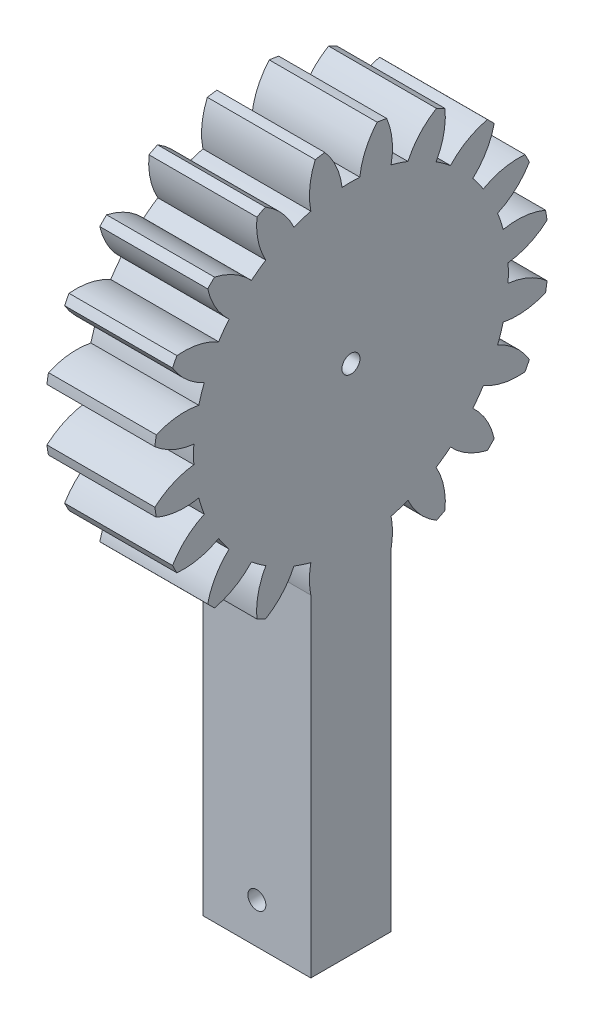
SolidWorks part; units mm, degrees
ref_plane "Plane1" through (0, 0, 0) normal (0, 0, 1) x (1, 0, 0)
ref_plane "Plane2" through (0, 0, 0) normal (0, 1, 0) x (1, 0, 0)
ref_plane "Plane3" through (0, 0, 0) normal (1, 0, 0) x (0, 0, -1)
other "Configuration Table"
sketch "HoldingSke" plane through (0, 0, 0) normal (0, 1, 0) x (1, 0, 0)
  line L0 (0, 0) -> (0.1879, -0.0684)
  line L1 (-15, 0) -> (100, 0) construction
  line L2 (0, 0) -> (-2.1039, 2.3779)
  line L3 (0, 0) -> (-11.863, 4.5341)
  line L4 (0, 0) -> (8.1152, 2.9537)
  line L5 (0, 0) -> (-46.8476, -17.4728)
  line L6 (0, 0) -> (-24.8689, -16.7791)
  line L7 (-2.1039, 2.3779) -> (8.6586, 51.2059)
  line L8 (-76.2, 54.61) -> (-75.3, 54.61)
  line L9 (-71.009, 38.7566) -> (-53.1078, 45.2721)
  line L10 (-76.2, 71.12) -> (104.1128, 71.12)
  line L11 (0, 0) -> (-30, 0)
  line L12 (-76.2, 101.6) -> (-76.033, 101.6)
  line L13 (24.9733, 27.94) -> (52.9518, 28.4284)
  line L14 (24.9733, 27.94) -> (24.9743, 27.94)
  line L15 (24.9733, 27.94) -> (100.4006, 29.5858)
  line L16 (-63.627, -5) -> (-12.827, -5)
  circle A0 centre (0, 0) radius 2.5
  circle A1 centre (0, 0) radius 37.5
  circle A2 centre (0, 0) radius 37.5
  circle A3 centre (0, 0) radius 2.5
  dimension "MHD" = 75
  dimension "Hub_dia" = 75
  dimension "Bore" = 5
  dimension "MBD" = 5
  dimension "Num_teeth" = 20
  dimension "Pitch" = 0.2
  dimension "Overall_len" = 50
  dimension "Show_teeth" = 20
  dimension "Thickness" = 30
  dimension "OAL" = 50.0001
  dimension "T_dim" = 0.9
  dimension "Ap" = 20
  dimension "H" = 19.05
  dimension "Pitch_radius" = 180.3128
  dimension "Width" = 30
  dimension "Backlash" = 0.167
  dimension "Addendum_fac" = 1
  dimension "Dedendum_fac" = 1.25
  dimension "Clearance_fac" = 0.25
  dimension "Dedendum_add" = 0.001
  dimension "Module" = 5
sketch "BasProSke" plane through (0, 0, 0) normal (0, 1, 0) x (1, 0, 0)
  line L0 (-10, 0) -> (60, 0) construction
  line L1 (0, 0) -> (0, 55)
  line L2 (0, 0) -> (30, 0)
  line L3 (30, 0) -> (30, 55)
  line L4 (30, 55) -> (0, 55)
  dimension "Thickness" = 30
  dimension "Diameter" = 110
revolve "Base-Revolve" add sketch "BasProSke" angle 360 about L0
sketch "TooCutSke" plane through (0, 0, 0) normal (1, 0, 0) x (0, 0, -1)
  line L1 (0, 0) -> (0, 107) construction
  line L2 (0, 0) -> (-4.2151, 49.822) construction
  line L3 (0, 0) -> (-15.6021, 98.5081) construction
  line L4 (-4.2151, 49.822) -> (-7.8011, 49.254) construction
  arc A0 (2.4648, 43.6795) -> (-2.4648, 43.6795) centre (0, 0) ccw
  arc A1 (7.3009, 54.5389) -> (-7.3009, 54.5389) centre (0, 0) ccw
  circle A2 centre (0, 0) radius 50 construction
  circle A3 centre (0, 0) radius 46.9846 construction
  arc A4 (-2.4648, 43.6795) -> (-7.3009, 54.5389) centre (-22.3276, 41.3405) ccw
  arc A5 (7.3009, 54.5389) -> (2.4648, 43.6795) centre (22.3276, 41.3405) ccw
  dimension "Root_dia" = 87.498
  dimension "Overcut_dia" = 110.0508
  dimension "Pitch_dia" = 100
  dimension "Base_dia" = 93.9693
  dimension "Flank_rad" = 20
  dimension "Half_ang" = 9
  dimension "Half_CT" = 3.6307
extrude "ToothCut" cut sketch "TooCutSke" along normal through all
fillet "Breaks" [suppressed] radius 0.1
fillet "RootFillets" [suppressed] radius 1.251
pattern_circular "TeethCuts" count 20 over 360 about axis through (0, 0, 0) along (1, 0, 0) of "ToothCut", "RootFillets", "Breaks"
sketch "HubNeaOneSke" plane through (0, 0, 0) normal (-1, 0, 0) x (0, 0, 1)
  circle A0 centre (0, 0) radius 37.5
  dimension "Diameter" = 75
extrude "HubNearOne" [suppressed] add sketch "HubNeaOneSke" along normal blind 20.0001
sketch "HubNeaBotSke" plane through (0, 0, 0) normal (-1, 0, 0) x (0, 0, 1)
  circle A0 centre (0, 0) radius 37.5
  dimension "Diameter" = 75
extrude "HubNearBoth" [suppressed] add sketch "HubNeaBotSke" along normal blind 10
ref_plane "FarPln" through (30, 0, 0) normal (1, 0, 0) x (0, 0, -1)
sketch "HubFarSke" plane through (30, 0, 0) normal (1, 0, 0) x (0, 0, -1)
  circle A0 centre (0, 0) radius 37.5
  dimension "Diameter" = 75
extrude "HubFar" [suppressed] add sketch "HubFarSke" along normal blind 10
sketch "BorSke" plane through (0, 0, 0) normal (1, 0, 0) x (0, 0, -1)
  circle A0 centre (0, 0) radius 2.5
  dimension "Diameter" = 5
extrude "Bore" cut sketch "BorSke" along normal mid plane 100.0001
sketch "KeySke" plane through (0, 0, 0) normal (1, 0, 0) x (0, 0, -1)
  line L0 (-1, 0) -> (-1, 3.4)
  line L1 (-1, 3.4) -> (1, 3.4)
  line L2 (1, 3.4) -> (1, 0)
  line L3 (0, 0) -> (0, 34) construction
  line L4 (-1, 0) -> (1, 0)
  dimension "Offset" = 3.4
  dimension "Width" = 2
extrude "Keyway" [suppressed] cut sketch "KeySke" along normal mid plane 100.0001
pattern_circular "Keyway2" [suppressed] count 2 every 90 about axis through (-10, 0, 0) along (1, 0, 0)
sketch "草图6" plane through (30, 0, 0) normal (1, 0, 0) x (0, 0, -1)
  line L0 (-11.1535, -42.3034) -> (-11.1535, -142.3034)
  line L1 (-11.1535, -142.3034) -> (11.1535, -142.3034)
  line L2 (11.1535, -142.3034) -> (11.1535, -42.3034)
  line L3 (0, 50) -> (0, -50) construction
  circle A0 centre (0, 0) radius 43.749 construction
  arc A1 (-11.1535, -42.3034) -> (11.1535, -42.3034) centre (0, 0) ccw
  point P11 (0, 0)
  dimension "D2" = 90
  dimension "D3" = 11.1535
  dimension "D1" = 100
extrude "凸台-拉伸1" add sketch "草图6" against normal up to surface (30 mm away) up to face at (0, 0, -2.5)
sketch "草图7" plane through (0, 0, 11.1535) normal (0, 0, 1) x (1, 0, 0)
  line L0 (0, -142.3034) -> (30, -142.3034) construction
  circle A0 centre (15, -131.0195) radius 2.5
  dimension "D1" = 5
  dimension "D2" = 11.2838
extrude "切除-拉伸1" cut sketch "草图7" against normal through all
equation "' \"Module@HoldingSke\" = 6.35"
equation "' \"Num_teeth@HoldingSke\" = 12"
equation "' \"Ap@HoldingSke\" =  20"
equation "' \"Ap@HoldingSke\" = 20"
equation "' \"Width@HoldingSke\" = 0.5 * 25.4"
equation "' \"Hub_dia@HoldingSke\"= 1 * 25.4"
equation "' \"Hub_dia@HoldingSke\" = 1 * 25.4"
equation "' \"Overall_len@HoldingSke\" = 1.0 * 25.4"
equation "' \"Bore@HoldingSke\" = 0.75 * 25.4"
equation "' \"T_dim@HoldingSke\" = 0.1 * 25.4"
equation "' \"Width@KeySke\" = 0.25 * 25.4"
equation "' \"Show_teeth@HoldingSke\" = 13"
equation "' \"Backlash@HoldingSke\" = 0.009 * 25.4"
equation "' \"Addendum_fac@HoldingSke\" = 1.0"
equation "' \"Dedendum_fac@HoldingSke\" = 1.25"
equation "' \"Dedendum_add@HoldingSke\" = 0.00005 * 25.4"
equation "' \"Clearance_fac@HoldingSke\" = 0.25"
equation "\"Pitch@HoldingSke\" = 1 / \"Module@HoldingSke\""
equation "\"Overcut_dia@TooCutSke\" = (\"Num_teeth@HoldingSke\" + 2 * \"Addendum_fac@HoldingSke\") / \"Pitch@HoldingSke\" + 0.002 * 25.4"
equation "\"Pitch_dia@TooCutSke\" = \"Num_teeth@HoldingSke\" / \"Pitch@HoldingSke\""
equation "\"Base_dia@TooCutSke\" = \"Num_teeth@HoldingSke\" / \"Pitch@HoldingSke\" * cos((\"Ap@HoldingSke\"  * 3.14159265 / 180))"
equation "\"Root_dia@TooCutSke\" = (\"Num_teeth@HoldingSke\" + 2) / \"Pitch@HoldingSke\" - 2 * (\"Addendum_fac@HoldingSke\" + \"Dedendum_fac@HoldingSke\") / \"Pitch@HoldingSke\" - \"Dedendum_add@HoldingSke\" * 2"
equation "\"Half_ang@TooCutSke\" = 180 / \"Num_teeth@HoldingSke\""
equation "\"Half_CT@TooCutSke\" = \"Num_teeth@HoldingSke\" / \"Pitch@HoldingSke\" * sin((3.14159265 / 2 / \"Num_teeth@HoldingSke\")) / 2 - 7 * \"Backlash@HoldingSke\" / 4"
equation "\"Flank_rad@TooCutSke\" = \"Num_teeth@HoldingSke\" / \"Pitch@HoldingSke\" / 5"
equation "\"Radius@RootFillets\" = \"Clearance_fac@HoldingSke\" / \"Pitch@HoldingSke\" + \"Dedendum_add@HoldingSke\""
equation "\"Break_rad@Breaks\" = 0.02 / \"Pitch@HoldingSke\""
equation "\"Thickness@HoldingSke\" = \"Width@HoldingSke\""
equation "\"OAL@HoldingSke\" = \"Thickness@HoldingSke\""
equation "\"MHD@HoldingSke\" = (\"Num_teeth@HoldingSke\" + 2) / \"Pitch@HoldingSke\" - 2 * (\"Addendum_fac@HoldingSke\" + \"Dedendum_fac@HoldingSke\")  / \"Pitch@HoldingSke\" - \"Dedendum_add@HoldingSke\" * 2"
equation "\"MBD@HoldingSke\" = (\"Num_teeth@HoldingSke\" + 2) / \"Pitch@HoldingSke\" - 2 * (\"Addendum_fac@HoldingSke\" + \"Dedendum_fac@HoldingSke\")  / \"Pitch@HoldingSke\" - \"Dedendum_add@HoldingSke\" * 2 - 0.002 * 25.4"
equation "\"MHD@HoldingSke\" = ((sgn( \"MHD@HoldingSke\" - \"Hub_dia@HoldingSke\" )-1)*( \"MHD@HoldingSke\" - \"Hub_dia@HoldingSke\" ))/-2+ \"Hub_dia@HoldingSke\""
equation "\"MBD@HoldingSke\" = ((sgn( \"MBD@HoldingSke\" - \"Bore@HoldingSke\" )-1)*( \"MBD@HoldingSke\" - \"Bore@HoldingSke\" ))/-2+ \"Bore@HoldingSke\""
equation "\"OAL@HoldingSke\" = ((sgn( \"OAL@HoldingSke\" - \"Overall_len@HoldingSke\" )+1)*( \"OAL@HoldingSke\" - \"Overall_len@HoldingSke\" ))/2 + \"Overall_len@HoldingSke\" + 0.000002 * 25.4"
equation "\"Num_teeth@TeethCuts\" = int( \"Show_teeth@HoldingSke\" ) + 1"
equation "\"Num_teeth@TeethCuts\" = ((sgn( \"Num_teeth@TeethCuts\" - \"Num_teeth@HoldingSke\" )-1)*( \"Num_teeth@TeethCuts\" - \"Num_teeth@HoldingSke\" ))/-2+ \"Num_teeth@HoldingSke\""
equation "\"Num_teeth@TeethCuts\" = ((sgn( \"Num_teeth@TeethCuts\" - 2.0)+1)*( \"Num_teeth@TeethCuts\" - 2.0))/2 +2.0"
equation "\"Angle@TeethCuts\" = 360.0 / \"Num_teeth@HoldingSke\""
equation "\"Diameter@BasProSke\" = (\"Num_teeth@HoldingSke\" + 2 * \"Addendum_fac@HoldingSke\") / \"Pitch@HoldingSke\""
equation "\"Thickness@BasProSke\"  = \"Thickness@HoldingSke\""
equation "' \"Fillet_rad@BasProSke\" =  \"Thickness@HoldingSke\" * 0.05"
equation "' \"Fillet_rad@BasProSke\" = \"Thickness@HoldingSke\" * 0.05"
equation "\"MHD@HoldingSke\" = ((sgn( \"MHD@HoldingSke\" - \"Root_dia@TooCutSke\" )-1)*( \"MHD@HoldingSke\" - \"Root_dia@TooCutSke\" ))/-2+ \"Root_dia@TooCutSke\""
equation "\"Diameter@HubNeaOneSke\" = \"MHD@HoldingSke\""
equation "\"Length@HubNearOne\" = \"OAL@HoldingSke\" - \"Thickness@BasProSke\""
equation "\"Diameter@HubNeaBotSke\" = \"MHD@HoldingSke\""
equation "\"Length@HubNearBoth\" = ( \"OAL@HoldingSke\" - \"Thickness@BasProSke\" ) / 2.0"
equation "\"Thickness@FarPln\" = \"Thickness@BasProSke\""
equation "\"Diameter@HubFarSke\" = \"MHD@HoldingSke\""
equation "\"Length@HubFar\" = ( \"OAL@HoldingSke\" - \"Thickness@BasProSke\" ) / 2.0"
equation "\"Diameter@BorSke\" = \"MBD@HoldingSke\""
equation "\"D1@Bore\" = \"OAL@HoldingSke\" * 2.0"
equation "\"D1@Keyway\" = \"OAL@HoldingSke\" * 2.0"
equation "\"Offset@KeySke\" = \"T_dim@HoldingSke\" + \"MBD@HoldingSke\" / 2.0"
